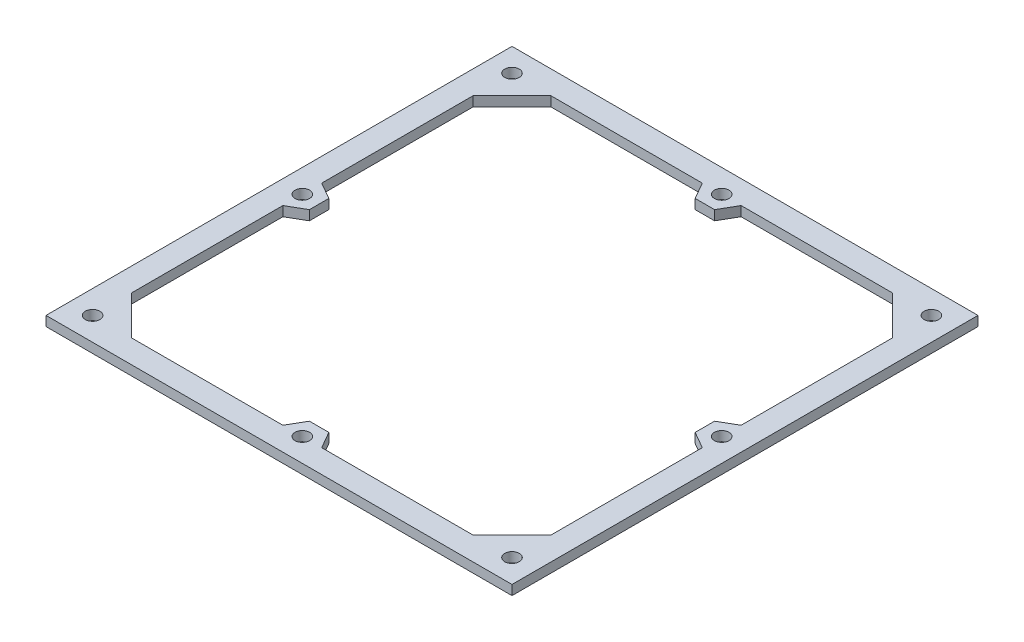
SolidWorks part; units mm, degrees
ref_plane "Front Plane" through (0, 0, 0) normal (0, 0, 1) x (1, 0, 0)
ref_plane "Top Plane" through (0, 0, 0) normal (0, 1, 0) x (1, 0, 0)
ref_plane "Right Plane" through (0, 0, 0) normal (1, 0, 0) x (0, 0, -1)
sketch "Sketch1" plane through (0, 0, 0) normal (0, 1, 0) x (1, 0, 0)
  line L0 (69.85, 7.62) -> (20.32, 7.62)
  line L1 (0, 0) -> (152.4, 0)
  line L2 (0, 0) -> (0, 152.4)
  line L3 (0, 152.4) -> (152.4, 152.4)
  line L4 (152.4, 0) -> (152.4, 152.4)
  line L5 (69.85, 144.78) -> (73.025, 139.2807)
  line L6 (73.025, 139.2807) -> (79.375, 139.2807)
  line L7 (79.375, 139.2807) -> (82.55, 144.78)
  line L8 (7.62, 132.08) -> (20.32, 144.78)
  line L9 (132.08, 144.78) -> (144.78, 132.08)
  line L10 (144.78, 20.32) -> (132.08, 7.62)
  line L11 (7.62, 20.32) -> (20.32, 7.62)
  line L12 (82.55, 144.78) -> (132.08, 144.78)
  line L13 (7.62, 20.32) -> (7.62, 69.85)
  line L14 (20.32, 144.78) -> (69.85, 144.78)
  line L15 (7.62, 82.55) -> (7.62, 132.08)
  line L16 (144.78, 69.85) -> (144.78, 20.32)
  line L17 (144.78, 132.08) -> (144.78, 82.55)
  line L19 (132.08, 7.62) -> (82.55, 7.62)
  line L21 (7.62, 69.85) -> (13.1193, 73.025)
  line L22 (82.55, 7.62) -> (79.375, 13.1193)
  line L23 (79.375, 13.1193) -> (73.025, 13.1193)
  line L24 (73.025, 13.1193) -> (69.85, 7.62)
  line L25 (71.4375, 4.8704) -> (73.3588, 1.5426) [skipped]
  line L26 (73.025, 2.1207) -> (80.7101, 2.1207) [skipped]
  line L27 (80.9625, 4.8704) -> (82.8838, 8.1981) [skipped]
  line L28 (74.1217, 152.1788) -> (72.2004, 148.851) [skipped]
  line L29 (81.5684, 150.2793) -> (73.8832, 150.2793) [skipped]
  line L30 (79.0881, 150.7763) -> (77.1668, 154.104) [skipped]
  line L31 (13.1193, 73.025) -> (13.1193, 79.375)
  line L32 (13.1193, 79.375) -> (7.62, 82.55)
  line L33 (144.78, 82.55) -> (139.2807, 79.375)
  line L34 (139.2807, 79.375) -> (139.2807, 73.025)
  line L35 (139.2807, 73.025) -> (144.78, 69.85)
  line L39 (153.5694, 74.9246) -> (153.7107, 75.0061) [skipped]
  line L40 (150.2793, 69.1237) -> (150.2793, 78.0856) [skipped]
  line L41 (153.6579, 77.4243) -> (153.5166, 77.5059) [skipped]
  line L42 (2.2208, 79.4328) -> (2.0796, 79.3512) [skipped]
  line L43 (2.1207, 79.375) -> (2.1207, 70.4131) [skipped]
  line L44 (2.1207, 73.025) -> (2.262, 72.9434) [skipped]
  circle A0 centre (7.62, 7.62) radius 2.3813
  circle A1 centre (7.62, 144.78) radius 2.3813
  circle A2 centre (144.78, 144.78) radius 2.3813
  circle A3 centre (144.78, 7.62) radius 2.3813
  circle A4 centre (76.2, 7.62) radius 2.3813
  circle A5 centre (76.2, 144.78) radius 2.3813
  circle A6 centre (144.78, 76.2) radius 2.3813
  circle A7 centre (7.62, 76.2) radius 2.3813
  dimension "D12" = 7.62
  dimension "D3" = 4.7625
  dimension "D6" = 4.7625
  dimension "D7" = 4.7625
  dimension "D8" = 4.7625
  dimension "D1" = 152.4
  dimension "D2" = 152.4
  dimension "D4" = 7.62
  dimension "D5" = 7.62
  dimension "D9" = 7.62
  dimension "D10" = 7.62
  dimension "D11" = 7.62
  dimension "D13" = 7.62
  dimension "D14" = 7.62
  dimension "D15" = 12.7
  dimension "D16" = 12.7
  dimension "D17" = 12.7
  dimension "D18" = 12.7
  dimension "D19" = 12.7
  dimension "D20" = 12.7
  dimension "D21" = 12.7
  dimension "D22" = 12.7
  dimension "D23" = 6.35
  dimension "D24" = 6.35
  dimension "D25" = 6.35
  dimension "D26" = 6.35
extrude "Boss-Extrude4" add sketch "Sketch1" along normal blind 3.175
